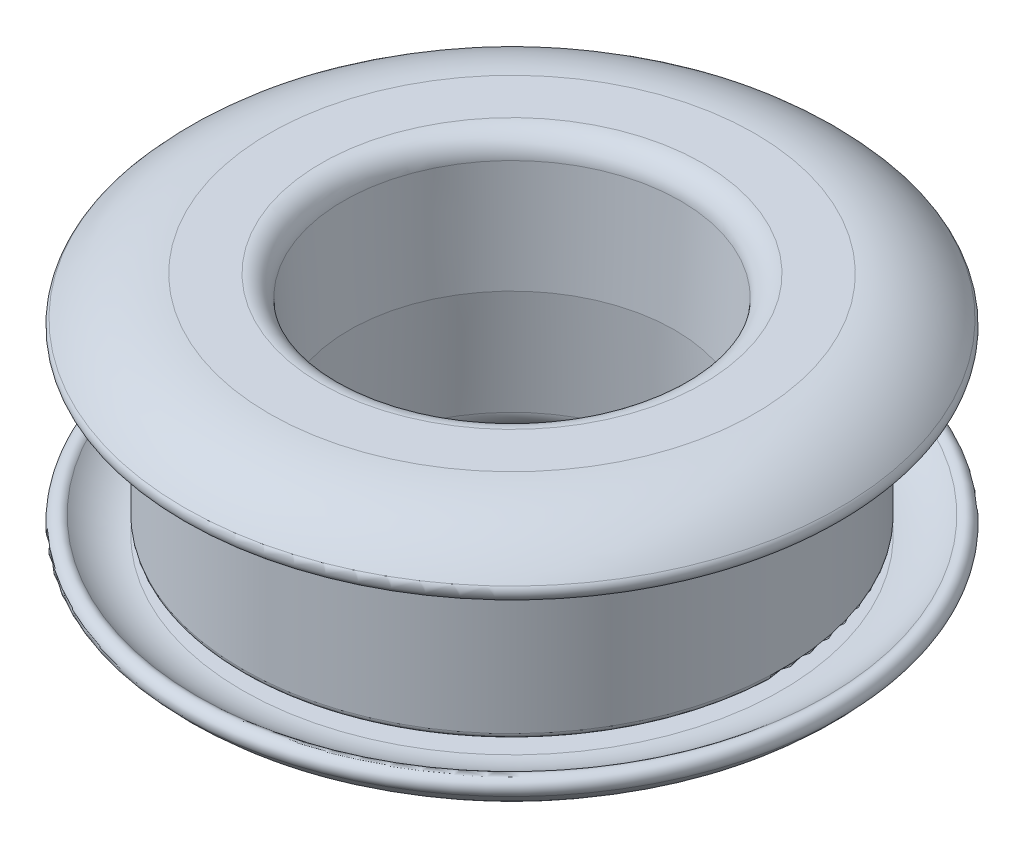
SolidWorks part; units mm, degrees
material "Smooth-Sil™ 940"
ref_plane "Front Plane" through (0, 0, 0) normal (0, 0, 1) x (1, 0, 0)
ref_plane "Top Plane" through (0, 0, 0) normal (0, 1, 0) x (1, 0, 0)
ref_plane "Right Plane" through (0, 0, 0) normal (1, 0, 0) x (0, 0, -1)
sketch "Sketch1" plane through (0, 0, 0) normal (0, 0, 1) x (1, 0, 0)
  line L0 (0, 0) -> (0, 46.445) construction
  line L1 (0, 0) -> (71.9029, 0) construction
  line L3 (18.4041, 0) -> (19.05, 12.3249)
  line L5 (30.48, 0) -> (30.48, 9.398)
  line L6 (30.48, 9.398) -> (24.8205, 9.398)
  line L7 (24.8205, 10.8417) -> (30.48, 10.8417)
  line L8 (24.8205, 10.8417) -> (24.8205, 9.398) construction
  line L9 (24.8205, 10.1198) -> (21.1246, 10.1198) construction
  line L10 (18.4041, 0) -> (30.48, 0)
  line L11 (21.5865, 14.732) -> (27.4445, 14.732)
  arc A0 (24.8205, 9.398) -> (24.8205, 10.8417) centre (24.13, 10.1198) cw
  arc A1 (30.48, 10.8417) -> (35.56, 8.89) centre (30.48, 3.2545) cw
  arc A2 (35.56, 8.89) -> (37.0149, 10.3021) centre (36.2403, 9.6447) ccw
  arc A3 (27.4445, 14.732) -> (37.0149, 10.3021) centre (27.4445, 2.1791) cw
  arc A4 (21.5865, 14.732) -> (19.05, 12.3249) centre (21.5865, 12.192) ccw
  point P24 (19.05, 14.4636)
  dimension "D4" = 0.9989
  dimension "D7" = 0.508
  dimension "D9" = 1.016
  dimension "D11" = 8.3988
  dimension "D12" = 2.54
  dimension "D1" = 60.96
  dimension "D2" = 38.1
  dimension "D3" = 18.796
  dimension "D5" = 1.4437
  dimension "D6" = 48.26
  dimension "D8" = 71.12
  dimension "D10" = 14.478
  dimension "D13" = 12.192
  dimension "D14" = 3
  dimension "D15" = 38.1
  dimension "D16" = 3.8903
revolve "Revolve1" add sketch "Sketch1" angle 360 about L0
fillet "Fillet1" radius 0.635 1 edges at (0, 9.398, -30.48)
mirror "Mirror1" about plane through (0, 0, 0) normal (0, 1, 0) of "Fillet1", "Revolve1"
